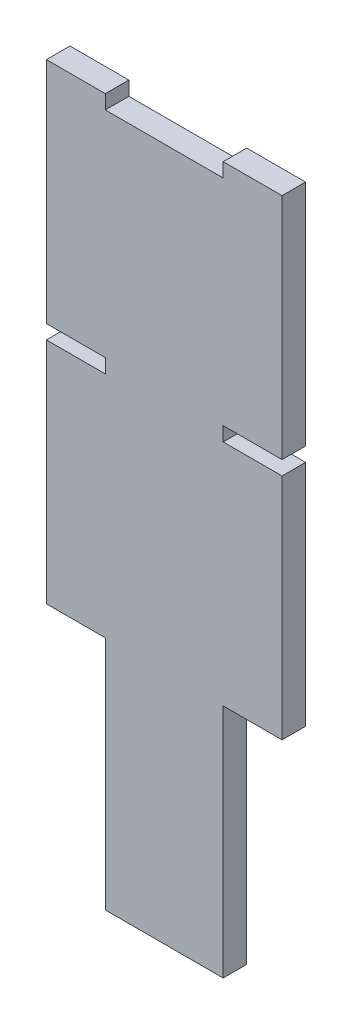
SolidWorks part; units mm, degrees
ref_plane "Front Plane" through (0, 0, 0) normal (0, 0, 1) x (1, 0, 0)
ref_plane "Top Plane" through (0, 0, 0) normal (0, 1, 0) x (1, 0, 0)
ref_plane "Right Plane" through (0, 0, 0) normal (1, 0, 0) x (0, 0, -1)
sketch "Sketch2" plane through (0, 0, 0) normal (0, 0, 1) x (1, 0, 0)
  line L1 (-25, 75) -> (25, 75)
  line L2 (-25, 75) -> (-25, -75)
  line L3 (-25, -75) -> (25, -75)
  line L4 (25, 75) -> (25, -75)
  line L5 (-25, 75) -> (25, -75) construction
  line L6 (-25, -75) -> (25, 75) construction
  point P0 (0, 0)
  dimension "D1" = 150
  dimension "D2" = 50
extrude "Boss-Extrude1" add sketch "Sketch2" along normal blind 5
sketch "Sketch3" plane through (0, 0, 5) normal (0, 0, 1) x (1, 0, 0)
  line L0 (0, 0) -> (50000, 0) construction
  line L1 (6.8137, 75) -> (50006.8137, 75) construction
  line L3 (25, 75) -> (-25, 75) construction
  line L4 (-52.656, 25) -> (49947.344, 25) construction
  line L5 (-56.5213, -25) -> (49943.4787, -25) construction
  line L6 (-42.7166, -75) -> (49957.2834, -75) construction
  line L7 (0, 0) -> (0, -50000) construction
  line L8 (-25, 75) -> (-25, -75) construction
  line L9 (-12.5, 75) -> (12.5, 75)
  line L10 (-12.5, 75) -> (-12.5, 72)
  line L11 (-12.5, 72) -> (12.5, 72)
  line L12 (12.5, 75) -> (12.5, 72)
  line L13 (-12.5, 75) -> (12.5, 72) construction
  line L14 (-12.5, 72) -> (12.5, 75) construction
  line L15 (-25, 26.5) -> (-12.5, 26.5)
  line L16 (-25, 26.5) -> (-25, 23.5)
  line L17 (-25, 23.5) -> (-12.5, 23.5)
  line L18 (-12.5, 26.5) -> (-12.5, 23.5)
  line L19 (12.5, 26.5) -> (12.5, 23.5)
  line L20 (25, 26.5) -> (25, 23.5)
  line L21 (25, 23.5) -> (12.5, 23.5)
  line L22 (25, 26.5) -> (12.5, 26.5)
  line L23 (25, -75) -> (12.5, -75)
  line L24 (-25, -25) -> (-12.5, -25)
  line L25 (-25, -25) -> (-25, -75)
  line L26 (-25, -75) -> (-12.5, -75)
  line L27 (-12.5, -25) -> (-12.5, -75)
  line L28 (12.5, -25) -> (12.5, -75)
  line L29 (25, -25) -> (12.5, -25)
  line L30 (25, -25) -> (25, -75)
  point P15 (0, 73.5)
  dimension "D1" = 50
  dimension "D2" = 50
  dimension "D3" = 50
  dimension "D4" = 3
  dimension "D5" = 25
  dimension "D6" = 3
  dimension "D7" = 12.5
  dimension "D8" = 12.5
extrude "Cut-Extrude1" cut sketch "Sketch3" against normal blind 5
